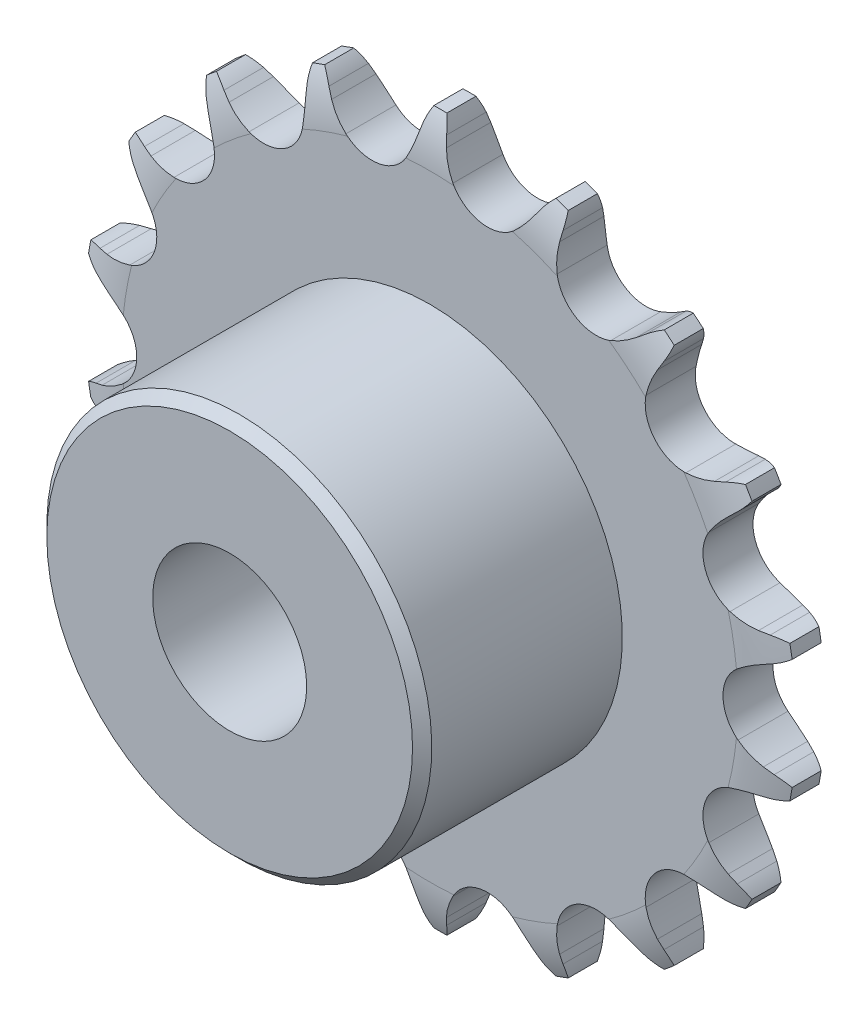
SolidWorks part; units mm, degrees
ref_plane "Front Plane" through (0, 0, 0) normal (0, 0, 1) x (1, 0, 0)
ref_plane "Top Plane" through (0, 0, 0) normal (0, 1, 0) x (1, 0, 0)
ref_plane "Right Plane" through (0, 0, 0) normal (1, 0, 0) x (0, 0, -1)
sketch "Sketch0" plane through (0, 0, 0) normal (0, 0, 1) x (1, 0, 0)
  line L0 (3, -17.0138) -> (0, 0) construction
  line L1 (0, 0) -> (8.6382, -14.9617) construction
  line L2 (0, 0) -> (-3, -17.0138) construction
  line L3 (3, -17.0138) -> (8.6382, -14.9617) construction
  line L4 (3, -17.0138) -> (-3, -17.0138) construction
  line L5 (5.5162, -16.9123) -> (5.2518, -16.5119)
  line L6 (3, -17.0138) -> (0, -17.5428) construction
  line L7 (0.6008, -17.779) -> (0.7124, -17.3124)
  line L8 (0, -17.0138) -> (0, -18.8138) construction
  line L9 (4.3616, -15.4839) -> (0.8727, -19.4043) construction
  line L10 (0, 0) -> (0, -17.0138) construction
  line L11 (5.2518, -16.5119) -> (0.8727, -19.4043) construction
  line L12 (0, -18.8138) -> (0, -19.0314) construction
  line L13 (8.2623, -15.0985) -> (5.5162, -16.9123) construction
  circle A0 centre (0, 0) radius 18.8138 construction
  circle A1 centre (0, 0) radius 17.2763 construction
  arc A2 (-3.0971, -20.2671) -> (9.8421, -17.9855) centre (0, 0) ccw
  circle A3 centre (0, 0) radius 19.0314 construction
  circle A4 centre (3, -17.0138) radius 2 construction
  arc A7 (4.3616, -15.4839) -> (1.1973, -16.0418) centre (3, -17.0138) ccw
  circle A8 centre (3, -17.0138) radius 2.0481 construction
  arc A9 (5.5162, -16.9123) -> (9.8421, -17.9855) centre (8.2623, -15.0985) ccw
  arc A10 (5.2518, -16.5119) -> (4.3616, -15.4839) centre (0.8727, -19.4043) ccw
  arc A11 (0.6008, -17.779) -> (-3.0971, -20.2671) centre (-2.6, -17.0138) cw
  arc A12 (0.7124, -17.3124) -> (1.1973, -16.0418) centre (5.8166, -18.5326) cw
  dimension "D1" = 2.0481
  dimension "Dr" = 4
  dimension "Ds" = 4.0962
  dimension "R" = 2.0481
  dimension "Pitch" = 6
  dimension "A" = 38.333
  dimension "360/N" = 20
  dimension "B" = 14.889
  dimension "ab" = 5.6
  dimension "J" = 1.8
  dimension "ac" = 3.2
sketch "Sketch1" plane through (0, 0, 0) normal (1, 0, 0) x (0, 0, -1)
  line L0 (1.3, 0) -> (-1.3, 0)
  line L1 (-1.3, 0) -> (-1.3, 16.0014)
  line L2 (-1.3, 17.2763) -> (0, 17.2763) construction
  line L3 (-0.6, 18.8138) -> (0.6, 18.8138)
  line L5 (1.3, 16.0014) -> (1.3, 0)
  line L7 (0, 18.8138) -> (0, 0) construction
  line L8 (-1.3, 16.0014) -> (1.3, 16.0014) construction
  line L9 (0, 18.8138) -> (0, -18.8138) construction
  line L10 (-1.3, 16.0014) -> (-1.3, 18.8138) construction
  line L11 (-1.3, 18.8138) -> (-0.6, 18.8138) construction
  line L12 (0.6, 18.8138) -> (1.3, 18.8138) construction
  line L13 (1.3, 18.8138) -> (1.3, 16.0014) construction
  line L14 (0, 0) -> (-6.4008, 0) construction
  line L15 (-1.3, 17.2763) -> (-1.3, 13.1763) construction
  line L22 (1.3, 0) -> (-11.7, 0) construction
  line L24 (-1.3, 0) -> (-1.3, 13.1763) construction
  arc A0 (-0.6, 18.8138) -> (-1.3, 16.0014) centre (4.7, 16.0014) ccw
  arc A1 (0.6, 18.8138) -> (1.3, 16.0014) centre (-4.7, 16.0014) cw
  dimension "R" = 6
  dimension "t" = 2.6
  dimension "C" = 0.7
  dimension "A" = 2.8125
  dimension "K" = 6.4008
  dimension "Width" = 13
  dimension "H" = 4.1
revolve "Revolve1" add sketch "Sketch1" angle 360 about L0
extrude "Cut-Extrude1" cut sketch "Sketch0" against normal through all and the other way through all
pattern_circular "CirPattern1" count 18 over 360 about axis through (0, 0, 0) along (0, 0, 1) of "Cut-Extrude1"
sketch "Sketch2" plane through (0, 0, 0) normal (0, 0, 1) x (1, 0, 0)
  circle A0 centre (0, 0) radius 4 construction
  circle A1 centre (0, 0) radius 10
  circle A2 centre (0, 0) radius 18.5 construction
  dimension "Bore" = 8
  dimension "Hub Dia." = 20
  dimension "OD" = 37
extrude "Boss-Extrude1" add sketch "Sketch2" along normal up to vertex (11.7 mm away) from surface at 1.3 starting at face at (0, 0, 1.3)
sketch "Sketch3" plane through (0, 0, 0) normal (0, 0, 1) x (1, 0, 0)
  circle A0 centre (0, 0) radius 4 construction
  circle A1 centre (0, 0) radius 4
extrude "Cut-Extrude2" cut sketch "Sketch3" along normal through all and the other way through all
sketch "Sketch4" plane through (0, 0, 0) normal (1, 0, 0) x (0, 0, -1)
  line L0 (-11.7, 10) -> (-11.7, 9.5)
  line L1 (-1.3, 18.8138) -> (-3.25, 18.8138)
  line L2 (-1.3, 18.8138) -> (-1.3, 13.1763)
  line L3 (-1.3, 13.1763) -> (-3.25, 13.1763)
  line L4 (-3.25, 18.8138) -> (-3.25, 13.1763)
  line L9 (-11.7, 9.5) -> (-11.2, 10)
  line L10 (-11.2, 10) -> (-11.7, 10)
  dimension "C" = 0.5
  dimension "D3" = 1.95
revolve "Cut-Revolve1" cut sketch "Sketch4" angle 360 about L22
sketch "Sketch5" plane through (0, 0, 0) normal (0, 0, 1) x (1, 0, 0)
  circle A0 centre (0, 0) radius 18.5 construction
  circle A1 centre (0, 0) radius 18.5
extrude "Cut-Extrude3" cut sketch "Sketch5" against normal through all and the other way through all flip side to cut
equation "\"360/N@Sketch0\" = 360/\"Teeth@CirPattern1\""
equation "\"Ds@Sketch0\" = 1.005 * \"Dr@Sketch0\" + ( 0.003 * 25.4 ) "
equation "\"R@Sketch0\" = 1/2 * \"Ds@Sketch0\""
equation "\"A@Sketch0\" = 35 +  ( 60 / \"Teeth@CirPattern1\" ) "
equation "\"B@Sketch0\" = 18 -  ( 56 / \"Teeth@CirPattern1\" )"
equation "\"ac@Sketch0\" = 0.8 * \"Dr@Sketch0\""
equation "\"ab@Sketch0\" = 1.4 * \"Dr@Sketch0\""
equation "\"J@Sketch0\" = 0.3 * \"Pitch@Sketch0\""
equation "\"D3@Sketch4\" = \"t@Sketch1\" * 3 / 4"
